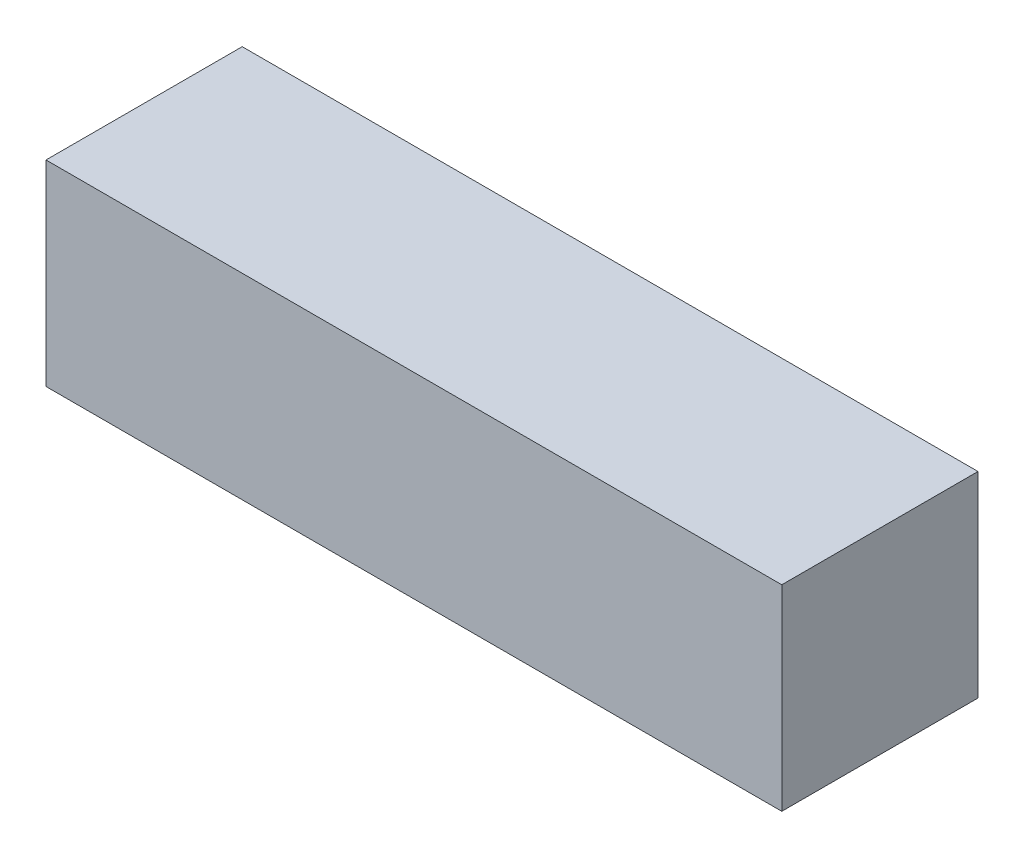
SolidWorks part; units mm, degrees
ref_plane "Front Plane" through (0, 0, 0) normal (0, 0, 1) x (1, 0, 0)
ref_plane "Top Plane" through (0, 0, 0) normal (0, 1, 0) x (1, 0, 0)
ref_plane "Right Plane" through (0, 0, 0) normal (1, 0, 0) x (0, 0, -1)
sketch "Sketch1" plane through (0, 0, 0) normal (0, 1, 0) x (1, 0, 0)
  line L1 (0, 0) -> (150, 0)
  line L2 (0, 0) -> (0, 40)
  line L3 (0, 40) -> (150, 40)
  line L4 (150, 0) -> (150, 40)
  point P5 (151.9237, 71.2142)
extrude "Boss-Extrude1" add sketch "Sketch1" along normal blind 40
